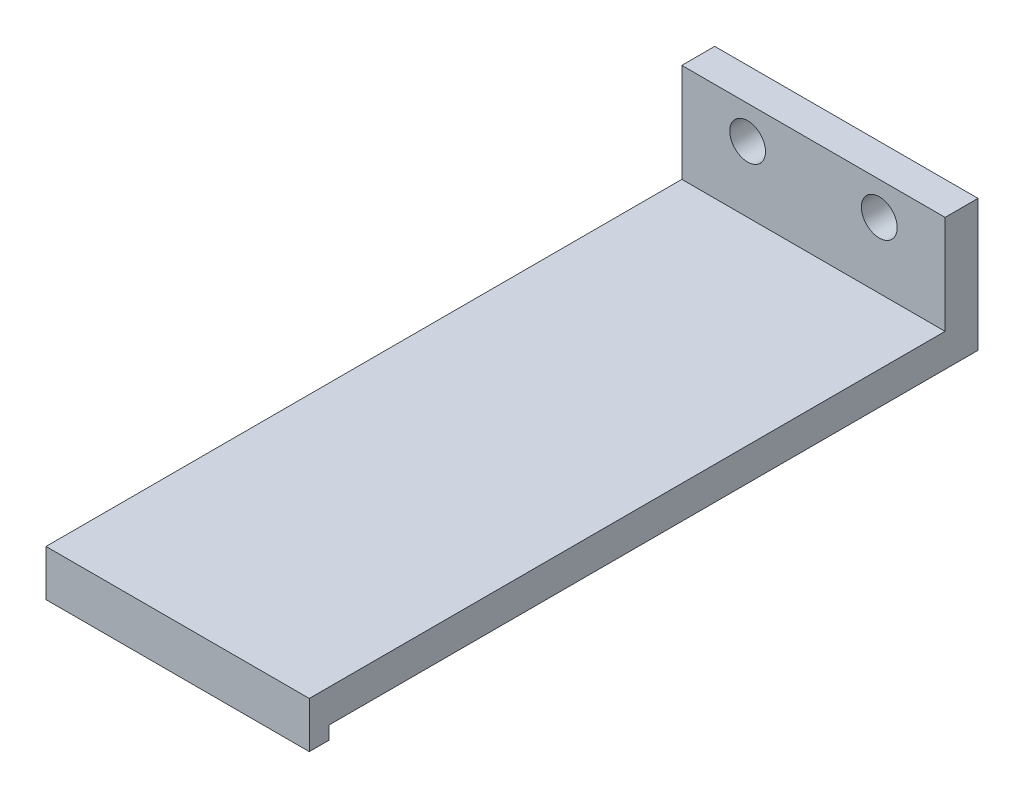
SolidWorks part; units mm, degrees
ref_plane "Front" through (0, 0, 0) normal (0, 0, 1) x (1, 0, 0)
ref_plane "Top" through (0, 0, 0) normal (0, 1, 0) x (1, 0, 0)
ref_plane "Right" through (0, 0, 0) normal (1, 0, 0) x (0, 0, -1)
sketch "Sketch1" plane through (0, 0, 0) normal (0, 0, 1) x (1, 0, 0)
  line L1 (-8.309, 5.5731) -> (17.091, 5.5731)
  line L2 (-8.309, 5.5731) -> (-8.309, -7.1269)
  line L3 (-8.309, -7.1269) -> (17.091, -7.1269)
  line L4 (17.091, 5.5731) -> (17.091, -7.1269)
  dimension "D1" = 12.7
  dimension "D2" = 25.4
extrude "Boss-Extrude1" add sketch "Sketch1" along normal blind 3.175
sketch "Sketch2" plane through (0, 0, 3.175) normal (0, 0, 1) x (1, 0, 0)
  line L0 (4.391, 5.5731) -> (4.391, -7.1269)
  line L1 (4.391, 5.5731) -> (-8.309, 5.5731)
  line L2 (-1.959, 5.5731) -> (-1.959, -7.1269)
  line L3 (4.391, 5.5731) -> (17.091, 5.5731)
  line L4 (-8.309, 5.5731) -> (-8.309, -7.1269)
  line L5 (-8.309, -7.1269) -> (17.091, -7.1269)
  line L6 (17.091, -7.1269) -> (17.091, 5.5731)
  line L7 (17.091, 5.5731) -> (-8.309, 5.5731)
  line L8 (-8.309, 5.5731) -> (-8.309, -7.1269)
  line L9 (-8.309, -7.1269) -> (17.091, -7.1269)
  line L10 (17.091, -7.1269) -> (17.091, 5.5731)
  line L11 (17.091, 5.5731) -> (-8.309, 5.5731)
  line L12 (10.741, 5.5731) -> (10.741, -7.1269)
  circle A2 centre (10.741, 2.3981) radius 1.7272
  circle A3 centre (-1.959, 2.3981) radius 1.7272
  dimension "D2" = 3.175
  dimension "D3" = 3.175
  dimension "D1" = 0
extrude "Cut-Extrude1" cut sketch "Sketch2" against normal blind 3.175 contours L12 A2 | L12 A2 | L2 A3 | L2 A3
sketch "Sketch3" plane through (0, 0, 3.175) normal (0, 0, 1) x (1, 0, 0)
  line L0 (17.091, -7.1269) -> (17.091, 5.5731) construction
  line L1 (-8.309, -7.1269) -> (17.091, -7.1269)
  line L2 (-8.309, -7.1269) -> (-8.309, -3.9519)
  line L3 (-8.309, -3.9519) -> (17.091, -3.9519)
  line L4 (17.091, -7.1269) -> (17.091, -3.9519)
  dimension "D1" = 3.175
extrude "Boss-Extrude2" add sketch "Sketch3" along normal up to surface (61.341 mm away)
sketch "Sketch4" plane through (0, -7.1269, 0) normal (0, -1, 0) x (1, 0, 0)
  line L0 (17.091, 64.516) -> (17.091, 0) construction
  line L1 (-8.309, 64.516) -> (17.091, 64.516)
  line L2 (-8.309, 64.516) -> (-8.309, 62.611)
  line L3 (-8.309, 62.611) -> (17.091, 62.611)
  line L4 (-8.055, 62.611) -> (16.837, 62.611)
  line L5 (-8.055, 64.516) -> (-8.055, 62.611)
  line L6 (16.837, 64.516) -> (-8.055, 64.516)
  line L7 (16.837, 62.611) -> (16.837, 64.516)
  line L8 (-8.055, 62.611) -> (16.837, 62.611)
  line L9 (-8.055, 64.516) -> (-8.055, 62.611)
  line L10 (16.837, 64.516) -> (-8.055, 64.516)
  line L11 (16.837, 62.611) -> (16.837, 64.516)
  line L12 (17.091, 64.516) -> (17.091, 62.611)
  dimension "D1" = 0
extrude "Boss-Extrude3" add sketch "Sketch4" along normal up to surface (1.27 mm away) contours L3 L12 L1 L2
